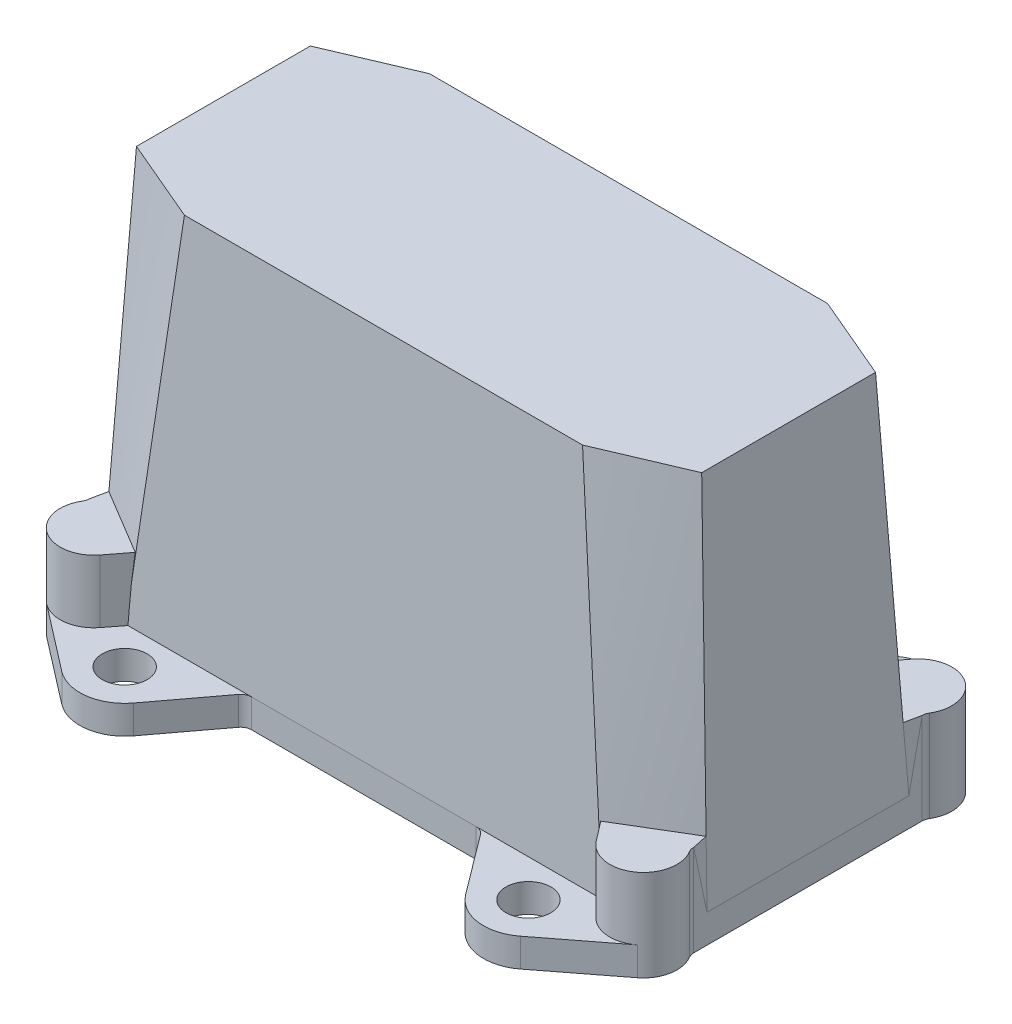
SolidWorks part; units mm, degrees
ref_plane "Front Plane" through (0, 0, 0) normal (0, 0, 1) x (1, 0, 0)
ref_plane "Top Plane" through (0, 0, 0) normal (0, 1, 0) x (1, 0, 0)
ref_plane "Right Plane" through (0, 0, 0) normal (1, 0, 0) x (0, 0, -1)
sketch "Sketch1" plane through (0, 0, 0) normal (0, 1, 0) x (1, 0, 0)
  line L0 (0, 45.3496) -> (0, -45.3496) construction
  line L1 (-18, 16) -> (18, 16) construction
  line L2 (-18, 16) -> (-18, -16) construction
  line L3 (-18, -16) -> (18, -16) construction
  line L4 (18, 16) -> (18, -16) construction
  line L5 (-18, 16) -> (18, -16) construction
  line L6 (-18, -16) -> (18, 16) construction
  line L8 (-26.925, 12.675) -> (26.925, 12.675)
  line L9 (-26.925, 12.675) -> (-26.925, -12.675)
  line L10 (-26.925, -12.675) -> (26.925, -12.675)
  line L11 (26.925, 12.675) -> (26.925, -12.675)
  circle A0 centre (-18, 16) radius 2
  circle A1 centre (18, 16) radius 2
  circle A2 centre (-18, -16) radius 2
  circle A3 centre (18, -16) radius 2
  point P0 (0, 0)
  point P12 (0, 12.675)
  point P13 (0, 0)
  point P18 (26.925, 0)
  dimension "D1" = 4
  dimension "D2" = 36
  dimension "D3" = 32
  dimension "D4" = 53.85
  dimension "D5" = 25.35
sketch "Sketch2" plane through (0, 0, 0) normal (0, 1, 0) x (1, 0, 0)
  line L1 (-24.5, 12.25) -> (24.5, 12.25) construction
  line L2 (-24.5, 12.25) -> (-24.5, -12.25) construction
  line L3 (-24.5, -12.25) -> (24.5, -12.25) construction
  line L4 (26.925, 12.675) -> (-26.925, 12.675)
  line L5 (-26.925, 12.675) -> (-26.925, -12.675)
  line L6 (-26.925, -12.675) -> (26.925, -12.675)
  line L7 (26.925, -12.675) -> (26.925, 12.675)
  line L8 (26.925, 12.675) -> (-26.925, 12.675)
  line L9 (-26.925, 12.675) -> (-26.925, -12.675)
  line L10 (-26.925, -12.675) -> (26.925, -12.675)
  line L11 (26.925, -12.675) -> (26.925, 12.675)
  line L12 (24.5, 12.25) -> (24.5, -12.25) construction
  circle A0 centre (18, 16) radius 4
  circle A1 centre (18, -16) radius 2
  circle A2 centre (18, -16) radius 2
  circle A3 centre (-18, -16) radius 2
  circle A4 centre (-18, -16) radius 2
  circle A5 centre (18, 16) radius 2
  circle A6 centre (18, 16) radius 2
  circle A7 centre (-18, 16) radius 2
  circle A8 centre (-18, 16) radius 2
  circle A9 centre (18, -16) radius 4
  circle A10 centre (-18, -16) radius 4
  circle A11 centre (-18, 16) radius 4
  circle A12 centre (-24.5, 12.25) radius 3
  circle A13 centre (-24.5, -12.25) radius 3
  circle A14 centre (24.5, -12.25) radius 3
  circle A15 centre (24.5, 12.25) radius 3
  point P28 (0, 12.25)
  point P30 (24.5, 0)
  point P35 (-27.5, 12.25)
  point P36 (27.5, 12.25)
  dimension "D9" = 55
  dimension "D7" = 49
  dimension "D8" = 24.5
  dimension "D1" = 0
  dimension "D2" = 0
  dimension "D3" = 0
  dimension "D4" = 0
  dimension "D5" = 0
  dimension "D6" = 2
sketch "Sketch3" plane through (0, 0, 0) normal (0, 1, 0) x (1, 0, 0)
  line L0 (-10.5, 12.675) -> (10.5, 12.675) construction
  line L1 (26.925, 12.675) -> (-26.925, 12.675) construction
  line L2 (-10.5, 12.675) -> (-14.8017, 18.4022)
  line L3 (10.5, 12.675) -> (14.8017, 18.4022)
  line L4 (-26.925, -12.675) -> (26.925, -12.675)
  line L5 (-26.925, 12.675) -> (-26.925, -12.675)
  line L6 (26.925, 12.675) -> (-26.925, 12.675)
  line L7 (26.925, -12.675) -> (26.925, 12.675)
  line L9 (-26.925, 10.4838) -> (-26.925, -10.4838)
  line L11 (26.925, -10.4838) -> (26.925, 10.4838)
  line L12 (-5.6128, 0) -> (5.6128, 0) construction
  line L13 (-26.3321, 14.6256) -> (-20.4428, 19.1675)
  line L14 (20.4428, 19.1675) -> (26.3321, 14.6256)
  line L15 (20.4428, -19.1675) -> (26.3321, -14.6256)
  line L16 (10.5, -12.675) -> (14.8017, -18.4022)
  line L17 (-10.5, -12.675) -> (-14.8017, -18.4022)
  line L18 (-26.3321, -14.6256) -> (-20.4428, -19.1675)
  line L19 (10.5, 12.675) -> (-10.5, 12.675)
  line L20 (-10.5, -12.675) -> (10.5, -12.675)
  circle A1 centre (-18, 16) radius 2
  circle A2 centre (-18, 16) radius 2
  circle A3 centre (18, 16) radius 2
  circle A4 centre (18, 16) radius 2
  circle A5 centre (-18, -16) radius 2
  circle A6 centre (-18, -16) radius 2
  circle A7 centre (18, -16) radius 2
  circle A8 centre (18, -16) radius 2
  circle A9 centre (-24.5, 12.25) radius 3
  arc A10 (-26.3321, 14.6256) -> (-26.925, 10.4838) centre (-24.5, 12.25) ccw
  circle A11 centre (-18, 16) radius 4
  arc A12 (-14.8017, 18.4022) -> (-20.4428, 19.1675) centre (-18, 16) ccw
  circle A13 centre (-18, -16) radius 4
  arc A14 (-20.4428, -19.1675) -> (-14.8017, -18.4022) centre (-18, -16) ccw
  circle A15 centre (18, -16) radius 4
  arc A16 (14.8017, -18.4022) -> (20.4428, -19.1675) centre (18, -16) ccw
  circle A17 centre (18, 16) radius 4
  arc A18 (20.4428, 19.1675) -> (14.8017, 18.4022) centre (18, 16) ccw
  circle A19 centre (24.5, 12.25) radius 3
  arc A20 (26.925, 10.4838) -> (26.3321, 14.6256) centre (24.5, 12.25) ccw
  circle A21 centre (24.5, -12.25) radius 3
  arc A22 (26.3321, -14.6256) -> (26.925, -10.4838) centre (24.5, -12.25) ccw
  circle A23 centre (-24.5, -12.25) radius 3
  arc A24 (-26.925, -10.4838) -> (-26.3321, -14.6256) centre (-24.5, -12.25) ccw
  point P47 (0, 12.675)
  point P52 (0, 0)
  dimension "D14" = 21
  dimension "D1" = 0
  dimension "D2" = 0
  dimension "D3" = 0
  dimension "D4" = 0
  dimension "D5" = 0
  dimension "D6" = 0
  dimension "D7" = 0
  dimension "D8" = 0
  dimension "D9" = 0
  dimension "D10" = 0
  dimension "D11" = 0
  dimension "D12" = 0
  dimension "D13" = 0
extrude "Boss-Extrude1" add sketch "Sketch3" along normal blind 2.54
fillet "Fillet1" radius 1 8 edges at (-26.925, 1.27, 10.4838) (-26.925, 1.27, -10.4838) (-10.5, 1.27, 12.675) (10.5, 1.27, 12.675) (-10.5, 1.27, -12.675) (26.925, 1.27, 10.4838) (26.925, 1.27, -10.4838) (10.5, 1.27, -12.675)
sketch "Sketch4" plane through (0, 2.54, 0) normal (0, 1, 0) x (1, 0, 0)
  line L0 (26.925, -12.675) -> (26.925, 12.675) construction
  line L1 (-26.925, -12.675) -> (26.925, -12.675) construction
  line L2 (-26.925, 12.675) -> (-26.925, -12.675) construction
  line L3 (26.925, 12.675) -> (-26.925, 12.675) construction
  line L4 (26.925, -12.675) -> (26.925, 12.675) construction
  line L5 (-26.925, -12.675) -> (26.925, -12.675) construction
  line L6 (-26.925, 12.675) -> (-26.925, -12.675) construction
  line L7 (26.925, 12.675) -> (-26.925, 12.675) construction
  line L8 (-21.25, -12.675) -> (21.25, -12.675) construction
  line L9 (26.925, 9) -> (26.925, -9) construction
  line L10 (-26.925, -9) -> (-21.25, -12.675)
  line L11 (21.25, -12.675) -> (26.925, -9)
  line L12 (-5.6128, 0) -> (5.6128, 0) construction
  line L13 (-5.6128, 0) -> (5.6128, 0) construction
  line L14 (21.25, 12.675) -> (26.925, 9)
  line L15 (-26.925, 9) -> (-21.25, 12.675)
  line L16 (-26.925, 9) -> (-26.925, -9)
  line L17 (-21.25, -12.675) -> (21.25, -12.675)
  line L18 (26.925, -9) -> (26.925, 9)
  line L19 (21.25, 12.675) -> (-21.25, 12.675)
  point P6 (0, -12.675)
  point P10 (26.925, 0)
  point P11 (-26.925, -9)
  dimension "D1" = 42.5
  dimension "D2" = 18
ref_plane "Plane1" through (0, 35, 0) normal (0, 1, 0) x (1, 0, 0)
sketch "Sketch5" plane through (0, 35, 0) normal (0, 1, 0) x (1, 0, 0)
  line L0 (26.925, -12.675) -> (26.925, 12.675) construction
  line L1 (-26.925, -12.675) -> (26.925, -12.675) construction
  line L2 (26.925, 12.675) -> (-26.925, 12.675) construction
  line L3 (-26.925, 12.675) -> (-26.925, -12.675) construction
  line L4 (26.925, -12.675) -> (26.925, 12.675) construction
  line L5 (-26.925, -12.675) -> (26.925, -12.675) construction
  line L6 (26.925, 12.675) -> (-26.925, 12.675) construction
  line L7 (-26.925, 12.675) -> (-26.925, -12.675) construction
  line L8 (-17.75, -10.925) -> (17.75, -10.925)
  line L9 (-25.2, 10.925) -> (25.2, 10.925) construction
  line L10 (-25.2, 10.925) -> (-25.2, -10.925) construction
  line L11 (-25.2, -10.925) -> (25.2, -10.925) construction
  line L12 (25.2, 10.925) -> (25.2, -10.925) construction
  line L13 (25.2, 7.75) -> (25.2, -7.75) construction
  line L14 (-25.2, -7.75) -> (-17.75, -10.925)
  line L15 (17.75, -10.925) -> (25.2, -7.75)
  line L16 (-5.6128, 0) -> (5.6128, 0) construction
  line L17 (-5.6128, 0) -> (5.6128, 0) construction
  line L18 (17.75, 10.925) -> (25.2, 7.75)
  line L19 (-25.2, 7.75) -> (-17.75, 10.925)
  line L20 (-25.2, 7.75) -> (-25.2, -7.75)
  line L21 (-17.75, 10.925) -> (17.75, 10.925)
  line L22 (25.2, 7.75) -> (25.2, -7.75)
  point P8 (0, 10.925)
  point P10 (25.2, 0)
  point P13 (0, -10.925)
  point P16 (25.2, 0)
  point P17 (-25.2, -7.75)
  dimension "D1" = 50.4
  dimension "D2" = 21.85
  dimension "D3" = 35.5
  dimension "D4" = 15.5
loft "Loft1" add profiles "Sketch4", "Sketch5"
sketch "Sketch7" plane through (0, 2.54, 0) normal (0, 1, 0) x (1, 0, 0)
  line L5 (-8.4767, 0) -> (8.4767, 0) construction
  line L6 (0, 6.6525) -> (0, -6.6525) construction
  line L7 (-22.1244, -14.0821) -> (-20.2923, -11.7065)
  line L8 (-26.925, 10.1838) -> (-26.925, 9) construction
  line L9 (-26.925, 10.1838) -> (-26.925, 6.5913)
  line L10 (-20.2923, 11.7065) -> (-26.925, 6.5913)
  line L11 (-20.2923, -11.7065) -> (-26.925, -6.5913)
  line L14 (-22.1244, 14.0821) -> (-20.2923, 11.7065)
  line L15 (-20.4428, 19.1675) -> (-26.3321, 14.6256) construction
  line L16 (-26.925, -10.1838) -> (-26.925, -6.5913)
  line L17 (26.925, -10.1838) -> (26.925, -6.5913)
  line L18 (20.2923, -11.7065) -> (26.925, -6.5913)
  line L19 (22.1244, -14.0821) -> (20.2923, -11.7065)
  line L20 (22.1244, 14.0821) -> (20.2923, 11.7065)
  line L21 (20.2923, 11.7065) -> (26.925, 6.5913)
  line L22 (26.925, 10.1838) -> (26.925, 6.5913)
  circle A3 centre (-24.5, 12.25) radius 3 construction
  arc A7 (-22.1244, 14.0821) -> (-27.0688, 10.7003) centre (-24.5, 12.25) ccw
  arc A8 (-26.925, 10.1838) -> (-27.0688, 10.7003) centre (-27.925, 10.1838) ccw construction
  arc A9 (-26.925, 10.1838) -> (-27.0688, 10.7003) centre (-27.925, 10.1838) ccw
  arc A12 (-26.925, -10.1838) -> (-27.0687, -10.7003) centre (-27.925, -10.1838) cw
  arc A13 (-22.1244, -14.0821) -> (-27.0687, -10.7003) centre (-24.5, -12.25) cw
  arc A14 (22.1244, -14.0821) -> (27.0687, -10.7003) centre (24.5, -12.25) ccw
  arc A15 (26.925, -10.1838) -> (27.0687, -10.7003) centre (27.925, -10.1838) ccw
  arc A16 (26.925, 10.1838) -> (27.0687, 10.7003) centre (27.925, 10.1838) cw
  arc A17 (22.1244, 14.0821) -> (27.0687, 10.7003) centre (24.5, 12.25) cw
  point P4 (0, 0)
  point P5 (0, 0)
extrude "Boss-Extrude2" add sketch "Sketch7" along normal blind 8.15 from surface at -2.54 starting at plane "Top Plane"
sketch "Sketch8" plane through (26.9838, 1.434, 0) normal (0.9986, 0.0531, 0) x (0, 0, -1)
  line L1 (-9, 1.1076) -> (9, 1.1076)
  line L2 (-8.784, 6.7255) -> (-7.75, 33.6134) construction
  line L3 (-9, 1.1076) -> (-7.75, 33.6134)
  line L4 (8.784, 6.7255) -> (7.75, 33.6134) construction
  line L5 (9, 1.1076) -> (7.75, 33.6134)
  line L6 (-6.5913, 1.1076) -> (6.5913, 1.1076) construction
  line L7 (-7.75, 33.6134) -> (7.75, 33.6134)
extrude "Cut-Extrude1" cut sketch "Sketch8" along normal through all
ref_plane "Plane2" through (23.9859, 1.0779, -5.1085) normal (0.9771, 0.0439, -0.2081) x (-0.2079, -0.0093, -0.9781)
sketch "Sketch9" plane through (23.9859, 1.0779, -5.1085) normal (0.9771, 0.0439, -0.2081) x (-0.2079, -0.0093, -0.9781)
  line L0 (-15.6346, 6.933) -> (-14.2035, 6.9464)
  line L1 (-14.2035, 6.9464) -> (-14.4243, 1.3286)
  line L2 (-14.4243, 1.3286) -> (-15.6346, 6.933)
extrude "Cut-Extrude2" cut sketch "Sketch9" along normal up to next
ref_plane "Plane3" through (23.9859, 1.0779, 5.1085) normal (0.9771, 0.0439, 0.2081) x (0.2079, 0.0093, -0.9781)
sketch "Sketch10" plane through (23.9859, 1.0779, 5.1085) normal (0.9771, 0.0439, 0.2081) x (0.2079, 0.0093, -0.9781)
  line L0 (14.4243, 1.3286) -> (15.6346, 6.933)
  line L1 (15.6346, 6.933) -> (14.2035, 6.9464)
  line L2 (14.2035, 6.9464) -> (14.4243, 1.3286)
extrude "Cut-Extrude3" cut sketch "Sketch10" along normal up to next
mirror "Mirror1" about plane through (0, 0, 0) normal (1, 0, 0) of "Cut-Extrude3", "Cut-Extrude1", "Cut-Extrude2"
ref_plane "Plane4" through (0, 0, 12.675) normal (0, 0, 1) x (1, 0, 0)
sketch "Sketch11" plane through (0, 0, 12.675) normal (0, 0, 1) x (1, 0, 0)
  line L0 (-10.0004, 0) -> (10.0004, 0) construction
  line L1 (-3.5, 17) -> (3.5, 17) construction
  line L2 (-3.5, 17) -> (-3.5, 10) construction
  line L3 (-3.5, 10) -> (3.5, 10) construction
  line L4 (3.5, 17) -> (3.5, 10) construction
  line L5 (-3.5, 13.5) -> (3.5, 13.5) construction
  circle A0 centre (0, 13.5) radius 1.8
  point P4 (0, 10)
  dimension "D4" = 3.6
  dimension "D1" = 10
  dimension "D2" = 7
  dimension "D3" = 7
ref_plane "Plane5" through (0, 0, -20) normal (0, 0, -1) x (-1, 0, 0)
ref_plane "Plane6" through (0, 0, 20) normal (0, 0, 1) x (1, 0, 0)
ref_plane "Plane7" through (0, 0, -12.675) normal (0, 0, -1) x (-1, 0, 0)
